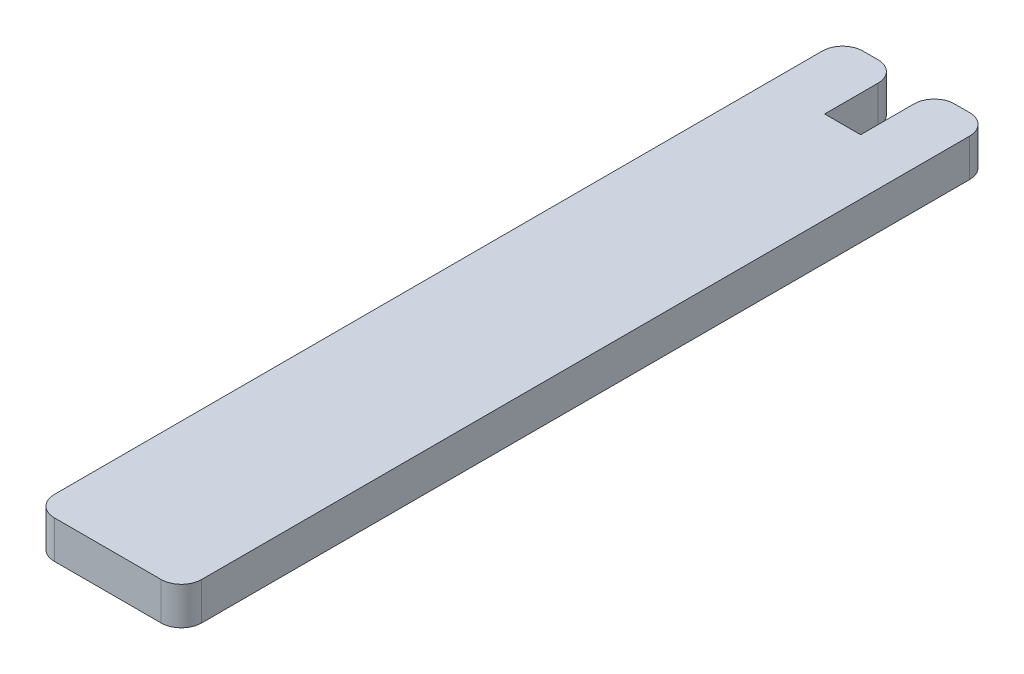
SolidWorks part; units mm, degrees
ref_plane "Front Plane" through (0, 0, 0) normal (0, 0, 1) x (1, 0, 0)
ref_plane "Top Plane" through (0, 0, 0) normal (0, 1, 0) x (1, 0, 0)
ref_plane "Right Plane" through (0, 0, 0) normal (1, 0, 0) x (0, 0, -1)
sketch "Sketch1" plane through (0, 0, 0) normal (0, 1, 0) x (1, 0, 0)
  line L0 (3.1, 69.7) -> (12.7, 69.7)
  line L1 (-12.7, 69.7) -> (-3.1, 69.7)
  line L2 (-12.7, 69.7) -> (-12.7, -69.7)
  line L3 (-12.7, -69.7) -> (12.7, -69.7)
  line L4 (12.7, 69.7) -> (12.7, -69.7)
  line L5 (-12.7, 69.7) -> (12.7, -69.7) construction
  line L6 (-12.7, -69.7) -> (12.7, 69.7) construction
  line L8 (-3.1, 69.7) -> (-3.1, 57)
  line L9 (-3.1, 57) -> (3.1, 57)
  line L10 (3.1, 69.7) -> (3.1, 57)
  point P0 (0, 0)
  point P10 (0, 57)
  dimension "D1" = 25.4
  dimension "D2" = 139.4
  dimension "D3" = 6.2
  dimension "D4" = 12.7
extrude "Boss-Extrude1" add sketch "Sketch1" along normal blind 6.5
fillet "Fillet1" radius 3.5 6 edges at (12.7, 3.25, 69.7) (-12.7, 3.25, 69.7) (3.1, 3.25, -69.7) (-3.1, 3.25, -69.7) (-12.7, 3.25, -69.7) (12.7, 3.25, -69.7)
